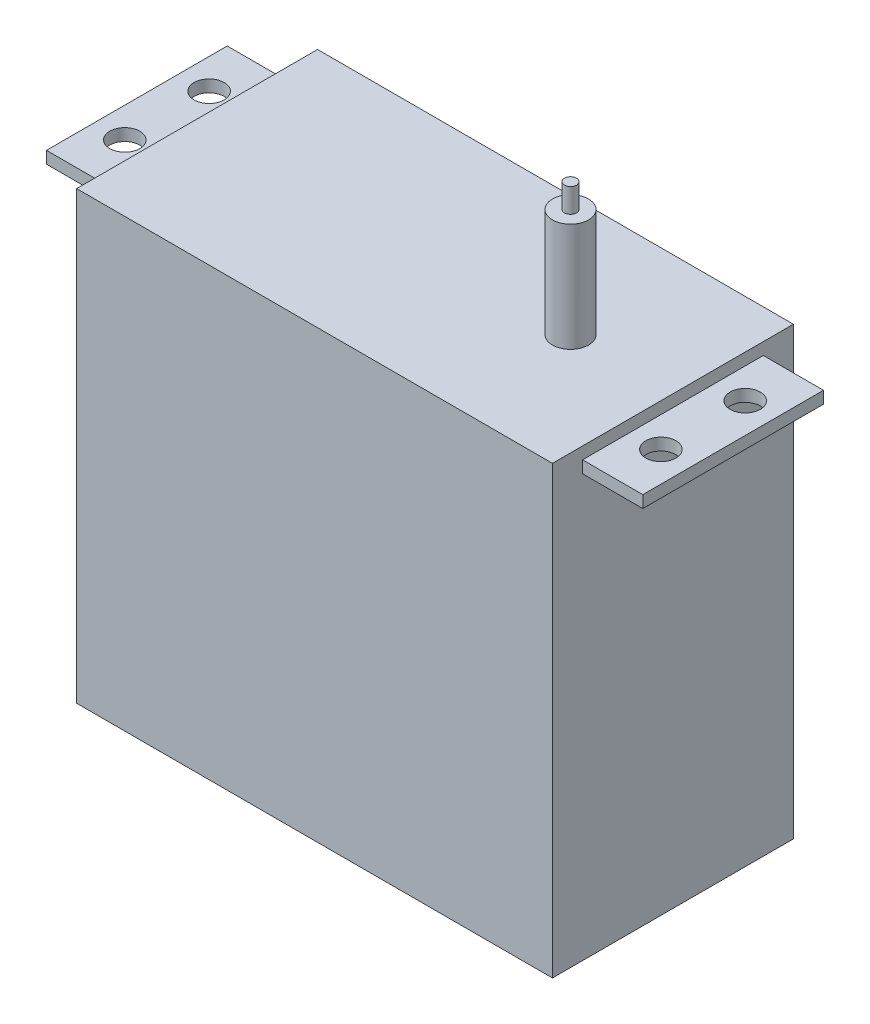
SolidWorks part; units mm, degrees
ref_plane "正面" through (0, 0, 0) normal (0, 0, 1) x (1, 0, 0)
ref_plane "平面" through (0, 0, 0) normal (0, 1, 0) x (1, 0, 0)
ref_plane "右側面" through (0, 0, 0) normal (1, 0, 0) x (0, 0, -1)
sketch "ｽｹｯﾁ1" plane through (0, 0, 0) normal (0, 1, 0) x (1, 0, 0)
  line L1 (0, 0) -> (39.5, 0)
  line L2 (0, 0) -> (0, 20)
  line L3 (0, 20) -> (39.5, 20)
  line L4 (39.5, 0) -> (39.5, 20)
  dimension "D1" = 39.5
  dimension "D2" = 20
extrude "ﾎﾞｽ - 押し出し1" add sketch "ｽｹｯﾁ1" along normal blind 37
sketch "ｽｹｯﾁ2" plane through (0, 37, 0) normal (0, 1, 0) x (1, 0, 0)
  circle A0 centre (31, 10) radius 1.5
extrude "ﾎﾞｽ - 押し出し2" add sketch "ｽｹｯﾁ2" along normal blind 9 contours A0
sketch "ｽｹｯﾁ3" plane through (0, 46, 0) normal (0, 1, 0) x (1, 0, 0)
  circle A0 centre (31, 10) radius 0.5
  dimension "D1" = 1
sketch "ｽｹｯﾁ14" plane through (39.5, 0, 0) normal (1, 0, 0) x (0, 0, -1)
  line L0 (20, 37) -> (20, 0) construction
  line L1 (17.5, 36) -> (2.5, 36)
  line L2 (17.5, 36) -> (17.5, 35)
  line L3 (17.5, 35) -> (2.5, 35)
  line L4 (2.5, 36) -> (2.5, 35)
  line L5 (0, 37) -> (20, 37) construction
  dimension "D1" = 15
  dimension "D2" = 1
  dimension "D3" = 2.5
  dimension "D4" = 1
extrude "ﾎﾞｽ - 押し出し5" add sketch "ｽｹｯﾁ14" along normal blind 5
sketch "ｽｹｯﾁ15" plane through (0, 0, 0) normal (-1, 0, 0) x (0, 0, 1)
  line L0 (0, -55) -> (0, 55) construction
  line L1 (-17.5, 35) -> (-2.5, 35)
  line L2 (-17.5, 35) -> (-17.5, 36)
  line L3 (-17.5, 36) -> (-2.5, 36)
  line L4 (-2.5, 35) -> (-2.5, 36)
  line L5 (-20, 37) -> (0, 37) construction
  dimension "D1" = 15
  dimension "D2" = 1
  dimension "D3" = 2.5
  dimension "D4" = 1
extrude "ﾎﾞｽ - 押し出し6" add sketch "ｽｹｯﾁ15" along normal blind 5
hole_wizard "M3x0.5 ねじ穴1" positions "ｽｹｯﾁ17" profile "ｽｹｯﾁ16" tap size "M3x0.5" standard "JIS"
sketch "ｽｹｯﾁ17" plane through (0, 36, 0) normal (0, 1, 0) x (1, 0, 0)
  line L0 (-5, 17.5) -> (0, 17.5) construction
  line L1 (-5, 2.5) -> (0, 2.5) construction
  line L2 (-5, 2.5) -> (-5, 17.5) construction
  line L3 (44.5, 17.5) -> (39.5, 17.5) construction
  line L4 (44.5, 17.5) -> (44.5, 2.5) construction
  line L5 (44.5, 2.5) -> (39.5, 2.5) construction
  line L6 (0, 17.5) -> (0, 2.5) construction
  point P0 (-2.5, 13.5)
  point P2 (-2.5, 6.5)
  point P4 (42, 6.5)
  point P6 (42, 13.5)
  point P11 (-2.5, 2.5)
  point P23 (42, 17.5)
  dimension "D1" = 4
  dimension "D2" = 4
  dimension "D3" = 2.5
  dimension "D4" = 2.5
  dimension "D5" = 4
  dimension "D6" = 2.5
  dimension "D7" = 2.5
  dimension "D8" = 4
  dimension "D9" = 2.5
  dimension "D10" = 7
sketch "ｽｹｯﾁ16" plane through (-2.5, 36, -13.5) normal (1, 0, 0) x (0, 0, 1)
  line L0 (0, 0) -> (0, 9.2511)
  line L1 (0, 9.2511) -> (1.25, 8.5)
  line L2 (1.25, 8.5) -> (1.25, 0)
  line L5 (1.25, 0) -> (0, 0)
  line L10 (0, 9.2511) -> (-1.25, 8.5) construction
  line L11 (0, -6.35) -> (0, 107.95) construction
  dimension "ねじ下穴ﾄﾞﾘﾙ直径" = 2.5
  dimension "ねじ下穴ﾄﾞﾘﾙの深さ" = 8.5
  dimension "ﾄﾞﾘﾙ角度" = 118
extrude "ﾎﾞｽ - 押し出し7" add sketch "ｽｹｯﾁ3" along normal blind 2
